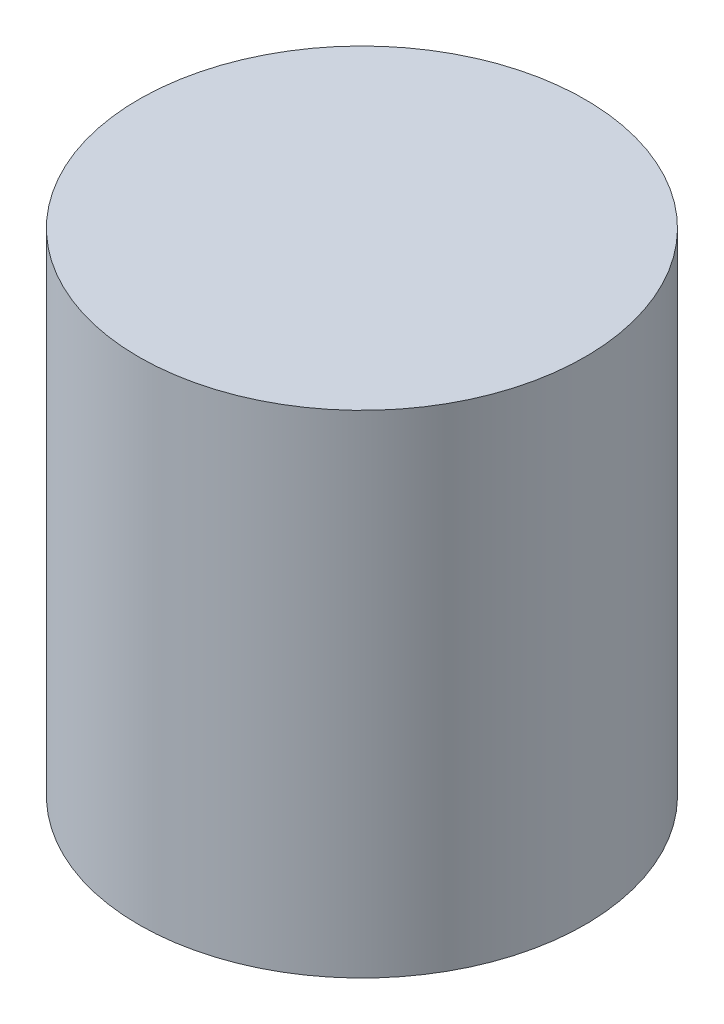
SolidWorks part; units mm, degrees
ref_plane "Front Plane" through (0, 0, 0) normal (0, 0, 1) x (1, 0, 0)
ref_plane "Top Plane" through (0, 0, 0) normal (0, 1, 0) x (1, 0, 0)
ref_plane "Right Plane" through (0, 0, 0) normal (1, 0, 0) x (0, 0, -1)
sketch "Sketch1" plane through (0, 0, 0) normal (0, 1, 0) x (1, 0, 0)
  circle A0 centre (0, 0) radius 29.5
extrude "Boss-Extrude1" add sketch "Sketch1" along normal blind 65 contours A0
sketch "Sketch2" plane through (0, 0, 0) normal (0, -1, 0) x (1, 0, 0)
  circle A0 centre (0, 0) radius 26
  circle A1 centre (0, 0) radius 29.5 construction
  dimension "D1" = 3.5
extrude "Cut-Extrude1" cut sketch "Sketch2" against normal blind 58.65
